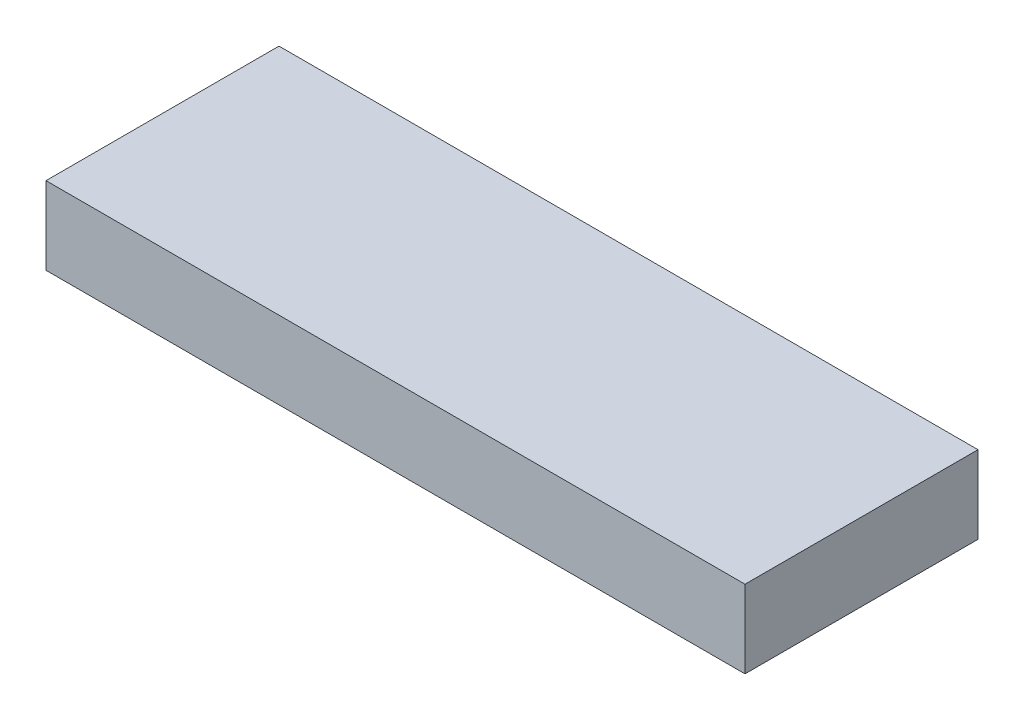
SolidWorks part; units mm, degrees
ref_plane "Front Plane" through (0, 0, 0) normal (0, 0, 1) x (1, 0, 0)
ref_plane "Top Plane" through (0, 0, 0) normal (0, 1, 0) x (1, 0, 0)
ref_plane "Right Plane" through (0, 0, 0) normal (1, 0, 0) x (0, 0, -1)
sketch "Sketch1" plane through (0, 0, 0) normal (0, 1, 0) x (1, 0, 0)
  line L1 (-45, -15) -> (45, -15)
  line L2 (-45, -15) -> (-45, 15)
  line L3 (-45, 15) -> (45, 15)
  line L4 (45, -15) -> (45, 15)
  line L5 (-45, -15) -> (45, 15) construction
  line L6 (-45, 15) -> (45, -15) construction
  point P0 (0, 0)
  dimension "D1" = 90
  dimension "D2" = 30
extrude "Boss-Extrude1" add sketch "Sketch1" along normal blind 10
